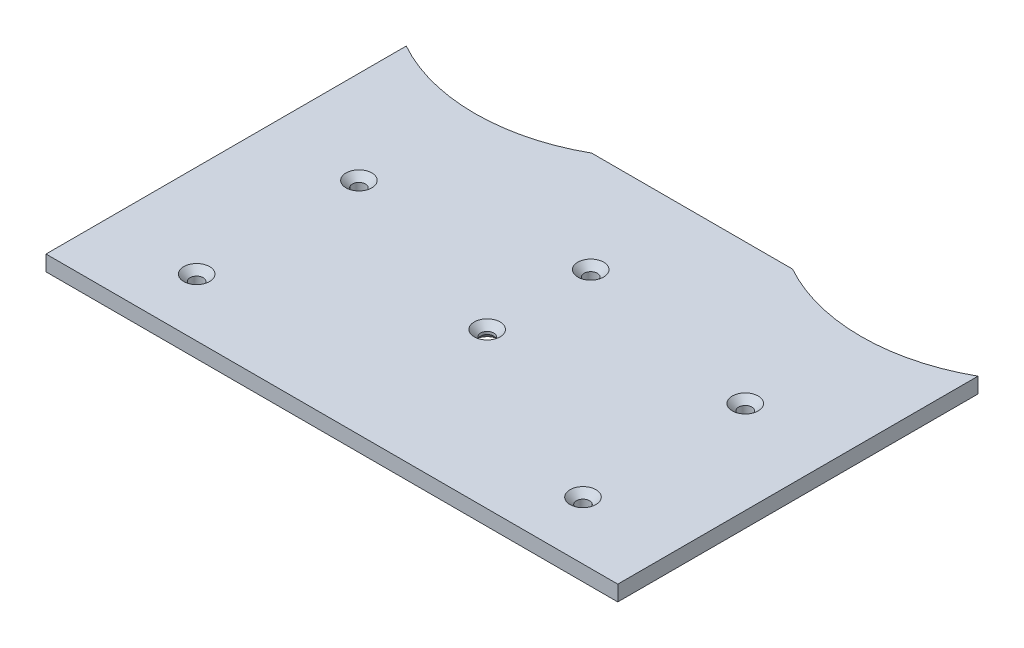
SolidWorks part; units mm, degrees
ref_plane "Front Plane" through (0, 0, 0) normal (0, 0, 1) x (1, 0, 0)
ref_plane "Top Plane" through (0, 0, 0) normal (0, 1, 0) x (1, 0, 0)
ref_plane "Right Plane" through (0, 0, 0) normal (1, 0, 0) x (0, 0, -1)
sketch "Sketch3" plane through (0, 0, 0) normal (0, 1, 0) x (1, 0, 0)
  line L2 (-50, 43.5) -> (50, 43.5) construction
  circle A0 centre (-50, 92.75) radius 49.25 construction
  circle A1 centre (50, 92.75) radius 49.25 construction
  dimension "D1" = 98.5
  dimension "D2" = 50
  dimension "D3" = 50
  dimension "D4" = 43.5
sketch "Sketch1" plane through (0, 0, 0) normal (0, 1, 0) x (1, 0, 0)
  line L0 (-74, 43.5) -> (-74, 49.7435)
  line L1 (-74, -43.5) -> (74, -43.5)
  line L2 (-74, -43.5) -> (-74, 43.5)
  line L4 (74, -43.5) -> (74, 43.5)
  line L5 (-74, -43.5) -> (74, 43.5) construction
  line L6 (-74, 43.5) -> (74, -43.5) construction
  line L7 (-26, 49.7435) -> (26, 49.7435)
  line L8 (74, 49.7435) -> (74, 43.5)
  arc A0 (-74, 49.7435) -> (-26, 49.7435) centre (-50, 92.75) ccw
  circle A1 centre (-50, 92.75) radius 49.25 construction
  arc A2 (74, 49.7435) -> (26, 49.7435) centre (50, 92.75) cw
  circle A3 centre (50, 92.75) radius 49.25 construction
  point P0 (0, 0)
  dimension "D1" = 148
  dimension "D2" = 87
extrude "Boss-Extrude1" add sketch "Sketch1" along normal blind 4
sketch "Sketch4" plane through (0, 4, 0) normal (0, 1, 0) x (1, 0, 0)
  line L1 (-74, -43.5) -> (74, -43.5) construction
  circle A0 centre (-50, -28.5) radius 1.7
  circle A1 centre (-50, 13.5) radius 1.7
  circle A2 centre (0, -3.3) radius 1.7
  circle A3 centre (0, 23.5) radius 1.7
  circle A4 centre (50, -28.5) radius 1.7
  circle A5 centre (50, 13.5) radius 1.7
  point P12 (0, 0)
  point P13 (0, 0)
  point P15 (0, 0)
  point P16 (0, 0)
  point P17 (0, 0)
  point P20 (0, 0)
  point P21 (0, 0)
  dimension "D1" = 3.4
  dimension "D2" = 42
  dimension "D3" = 50
  dimension "D4" = 25.2
  dimension "D5" = 26.8
  dimension "D6" = 100
  dimension "D7" = 15
extrude "Cut-Extrude1" cut sketch "Sketch4" against normal up to surface (4 mm away) up to face at (0, 0, -16.5812)
chamfer "Chamfer1" distance 1.65 angle 45 7 edges at (50, 4, 30.2) (50, 4, -11.8) (0, 4, -21.8) (0, 0, 5) (-50, 4, 30.2) (-50, 4, -11.8) (0, 4, 5)
